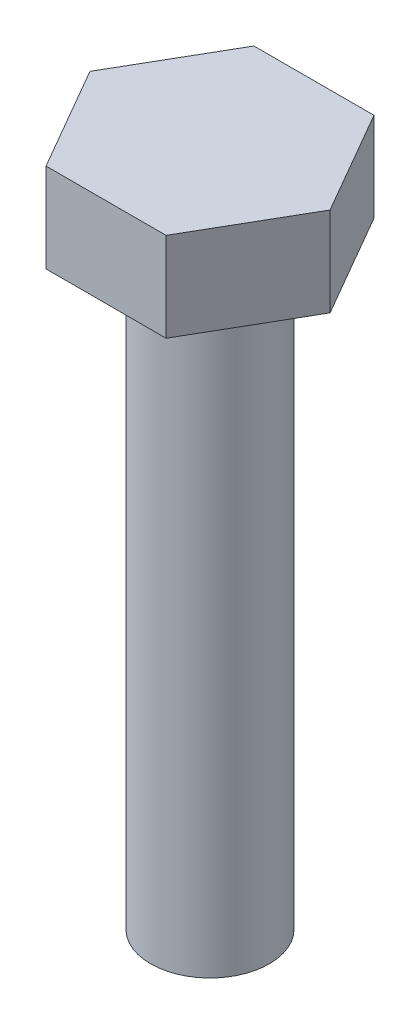
SolidWorks part; units mm, degrees
ref_plane "Front Plane" through (0, 0, 0) normal (0, 0, 1) x (1, 0, 0)
ref_plane "Top Plane" through (0, 0, 0) normal (0, 1, 0) x (1, 0, 0)
ref_plane "Right Plane" through (0, 0, 0) normal (1, 0, 0) x (0, 0, -1)
sketch "Sketch1" plane through (0, 0, 0) normal (0, 1, 0) x (1, 0, 0)
  circle A0 centre (0, 0) radius 2
  dimension "D1" = 4
extrude "Boss-Extrude1" add sketch "Sketch1" along normal blind 20
sketch "Sketch2" plane through (0, 20, 0) normal (0, 1, 0) x (1, 0, 0)
  line L1 (4.0415, 0) -> (2.0207, 3.5)
  line L2 (2.0207, 3.5) -> (-2.0207, 3.5)
  line L3 (-2.0207, 3.5) -> (-4.0415, 0)
  line L4 (-4.0415, 0) -> (-2.0207, -3.5)
  line L5 (-2.0207, -3.5) -> (2.0207, -3.5)
  line L6 (2.0207, -3.5) -> (4.0415, 0)
  circle A0 centre (0, 0) radius 3.5 construction
  point P1 (0, 0)
  dimension "D1" = 7
extrude "Boss-Extrude2" add sketch "Sketch2" along normal blind 3
